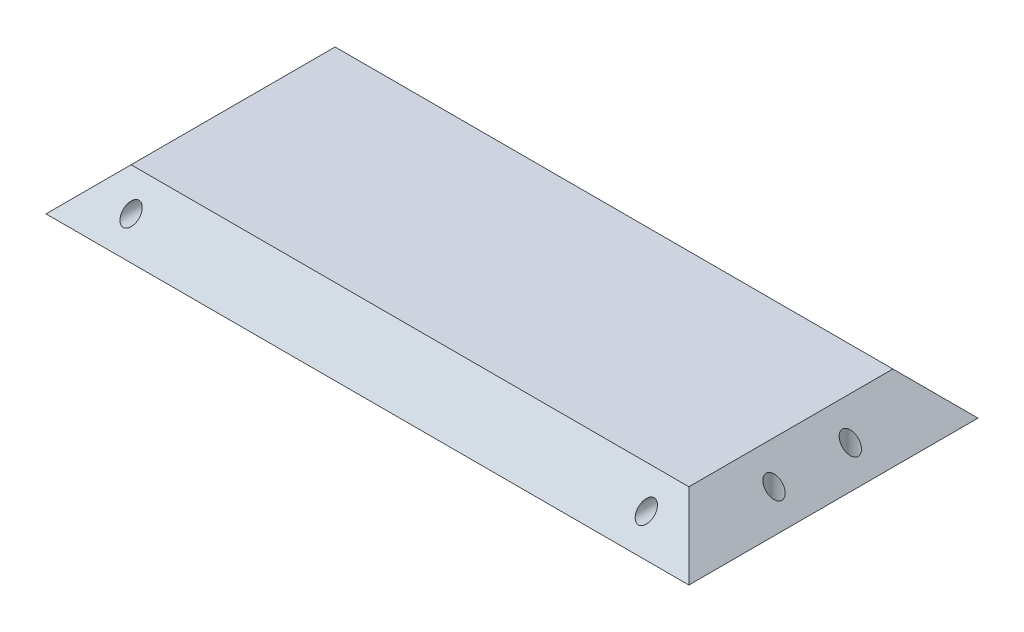
SolidWorks part; units mm, degrees
ref_plane "Спереди" through (0, 0, 0) normal (0, 0, 1) x (1, 0, 0)
ref_plane "Сверху" through (0, 0, 0) normal (0, 1, 0) x (1, 0, 0)
ref_plane "Справа" through (0, 0, 0) normal (1, 0, 0) x (0, 0, -1)
sketch "Эскиз1" plane through (0, 0, 0) normal (0, 1, 0) x (1, 0, 0)
  line L1 (-75.5296, -33.9663) -> (75.5296, -33.9663)
  line L2 (-75.5296, -33.9663) -> (-75.5296, 33.9663)
  line L3 (-75.5296, 33.9663) -> (75.5296, 33.9663)
  line L4 (75.5296, -33.9663) -> (75.5296, 33.9663)
  line L5 (-75.5296, -33.9663) -> (75.5296, 33.9663) construction
  line L6 (-75.5296, 33.9663) -> (75.5296, -33.9663) construction
  point P0 (0, 0)
  point P5 (-75.5296, -33.9663)
ref_plane "Плоскость1" through (0, 10, 0) normal (0, 1, 0) x (1, 0, 0)
sketch "Эскиз2" plane through (0, 10, 0) normal (0, 1, 0) x (1, 0, 0)
  line L4 (75.5296, -33.9663) -> (75.5296, 33.9663) construction
  line L5 (-75.5296, -33.9663) -> (75.5296, -33.9663) construction
  line L6 (-75.5296, -33.9663) -> (-75.5296, 33.9663) construction
  line L7 (-75.5296, 33.9663) -> (75.5296, 33.9663) construction
  line L8 (65.5296, -23.9663) -> (65.5296, 23.9663)
  line L9 (-65.5296, -23.9663) -> (65.5296, -23.9663)
  line L10 (-65.5296, 23.9663) -> (-65.5296, -23.9663)
  line L11 (65.5296, 23.9663) -> (-65.5296, 23.9663)
  line L12 (65.5296, -23.9663) -> (65.5296, 23.9663)
  line L13 (-65.5296, -23.9663) -> (65.5296, -23.9663)
  line L14 (-65.5296, 23.9663) -> (-65.5296, -23.9663)
  line L15 (65.5296, 23.9663) -> (-65.5296, 23.9663)
  line L16 (75.5296, -33.9663) -> (75.5296, 33.9663) construction
  line L17 (-75.5296, -33.9663) -> (75.5296, -33.9663) construction
  line L18 (-75.5296, -33.9663) -> (-75.5296, 33.9663) construction
  line L19 (-75.5296, 33.9663) -> (75.5296, 33.9663) construction
  line L20 (-65.5296, -23.9663) -> (-75.5296, -23.9663) construction
  line L21 (-65.5296, -23.9663) -> (-65.5296, -33.9663) construction
  line L22 (65.5296, -23.9663) -> (65.5296, -33.9663) construction
  line L23 (65.5296, -23.9663) -> (75.5296, -23.9663) construction
  line L24 (65.5296, 23.9663) -> (75.5296, 23.9663) construction
  line L25 (65.5296, 23.9663) -> (65.5296, 33.9663) construction
  line L26 (-65.5296, 23.9663) -> (-75.5296, 23.9663) construction
  line L27 (-65.5296, 23.9663) -> (-65.5296, 33.9663) construction
  dimension "D1" = 10
loft "По сечениям1" add profiles "Эскиз1", "Эскиз2"
ref_plane "Плоскость2" through (0, 0, 33.9663) normal (0, 0, 1) x (1, 0, 0)
sketch "Эскиз4" plane through (0, 0, 33.9663) normal (0, 0, 1) x (1, 0, 0)
  line L0 (-75.5296, 10) -> (-75.5296, 0) construction
  line L1 (75.5296, 0) -> (75.5296, 10) construction
  line L2 (-75.5296, 10) -> (75.5296, 10) construction
  line L3 (-75.5296, 10) -> (75.5296, 10) construction
  line L4 (-65.5296, 10) -> (-65.5296, 0) construction
  line L5 (-75.5296, 0) -> (75.5296, 0) construction
  line L6 (-55.5296, 10) -> (-55.5296, 0) construction
  line L7 (-65.5296, 5) -> (-55.5296, 5) construction
  line L8 (0, 0) -> (0, 10) construction
  circle A0 centre (-60.5296, 5) radius 1.85
  circle A1 centre (60.5296, 5) radius 1.85
  dimension "D2" = 3.7
  dimension "D1" = 10
extrude "Вырез-Вытянуть1" cut sketch "Эскиз4" against normal blind 20
mirror "Зеркальное отражение1" about plane through (0, 0, 0) normal (0, 0, 1) of "Вырез-Вытянуть1"
sketch "Эскиз5" plane through (0, 0, 0) normal (0, -1, 0) x (1, 0, 0)
  line L0 (65.5296, 23.9663) -> (65.5296, -23.9663) construction
  line L1 (-65.5296, 23.9663) -> (65.5296, 23.9663) construction
  line L2 (65.5296, -23.9663) -> (-65.5296, -23.9663) construction
  line L3 (-65.5296, -23.9663) -> (-65.5296, 23.9663) construction
  line L4 (65.5296, 23.9663) -> (65.5296, -23.9663) construction
  line L5 (-65.5296, 23.9663) -> (65.5296, 23.9663) construction
  line L6 (65.5296, -23.9663) -> (-65.5296, -23.9663) construction
  line L7 (-65.5296, -23.9663) -> (-65.5296, 23.9663) construction
  line L8 (-65.5296, 13.9663) -> (-75.5296, 13.9663) construction
  line L10 (-75.5296, 33.9663) -> (-75.5296, -33.9663) construction
  line L11 (-65.5296, 3.9663) -> (-75.5296, 3.9663) construction
  line L12 (0, -33.9663) -> (0, 33.9663) construction
  line L13 (-75.5296, -33.9663) -> (75.5296, -33.9663) construction
  line L14 (-75.5296, 33.9663) -> (75.5296, 33.9663) construction
  line L15 (-75.5296, 0) -> (75.5296, 0) construction
  line L16 (75.5296, 33.9663) -> (75.5296, -33.9663) construction
  line L17 (-70.5296, 13.9663) -> (-70.5296, 3.9663) construction
  circle A0 centre (-70.5296, 8.9663) radius 1.85
  circle A1 centre (-70.5296, -8.9663) radius 1.85
  circle A2 centre (70.5296, -8.9663) radius 1.85
  circle A3 centre (70.5296, 8.9663) radius 1.85
  dimension "D3" = 3.7
  dimension "D1" = 10
  dimension "D2" = 20
extrude "Вырез-Вытянуть2" cut sketch "Эскиз5" against normal through all contours A2 | A3 | A1 | A0
